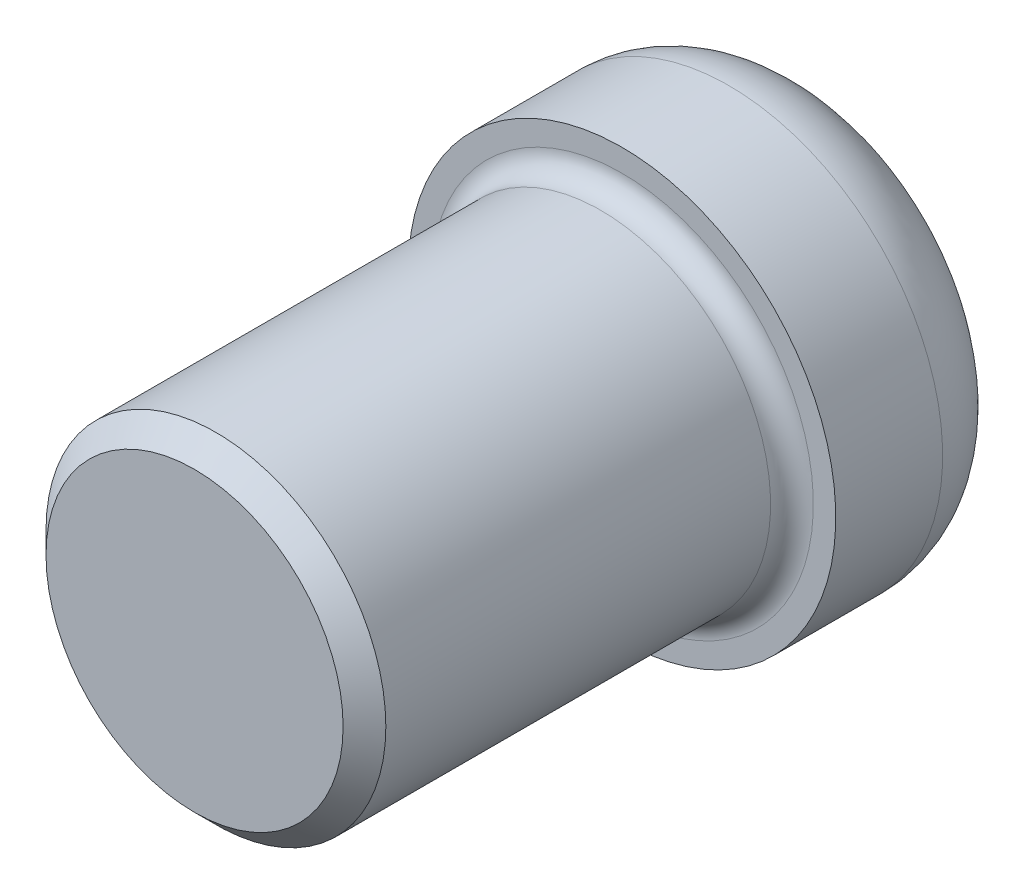
SolidWorks part; units mm, degrees
ref_plane "Front Plane" through (0, 0, 0) normal (0, 0, 1) x (1, 0, 0)
ref_plane "Top Plane" through (0, 0, 0) normal (0, 1, 0) x (1, 0, 0)
ref_plane "Right Plane" through (0, 0, 0) normal (1, 0, 0) x (0, 0, -1)
sketch "Sketch1" plane through (0, 0, 0) normal (0, 0, 1) x (1, 0, 0)
  circle A0 centre (0, 0) radius 3.975
  dimension "D1" = 7.95
extrude "Boss-Extrude1" add sketch "Sketch1" along normal blind 10
sketch "Sketch2" plane through (0, 0, 0) normal (0, 0, -1) x (-1, 0, 0)
  circle A0 centre (0, 0) radius 5
  dimension "D1" = 10
extrude "Boss-Extrude2" add sketch "Sketch2" along normal blind 4.5
fillet "Fillet1" radius 2 1 edges at (-5, 0, -4.5)
fillet "Fillet2" radius 0.5 1 edges at (-3.975, 0, 0)
chamfer "Chamfer1" distance 0.5 angle 45 1 edges at (3.975, 0, 10)
